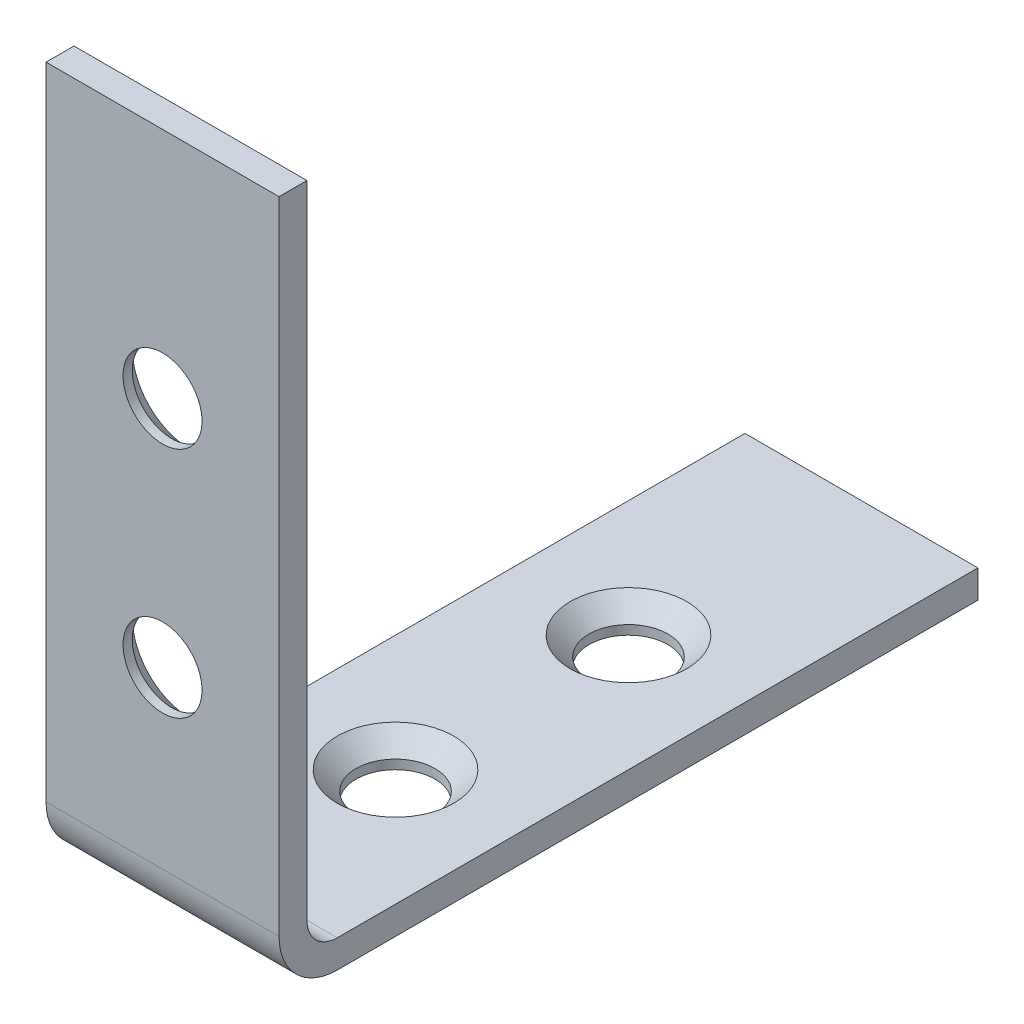
SolidWorks part; units mm, degrees
material "Galvanized Steel"
ref_plane "Front Plane" through (0, 0, 0) normal (0, 0, 1) x (1, 0, 0)
ref_plane "Top Plane" through (0, 0, 0) normal (0, 1, 0) x (1, 0, 0)
ref_plane "Right Plane" through (0, 0, 0) normal (1, 0, 0) x (0, 0, -1)
sketch "Sketch1" plane through (0, 0, 0) normal (1, 0, 0) x (0, 0, -1)
  line L0 (0, 3.175) -> (0, 38.1)
  line L1 (0, 38.1) -> (1.524, 38.1)
  line L2 (1.524, 38.1) -> (1.524, 3.175)
  line L3 (3.175, 1.524) -> (38.1, 1.524)
  line L4 (38.1, 1.524) -> (38.1, 0)
  line L5 (38.1, 0) -> (3.175, 0)
  arc A0 (0, 3.175) -> (3.175, 0) centre (3.175, 3.175) ccw
  arc A1 (1.524, 3.175) -> (3.175, 1.524) centre (3.175, 3.175) ccw
  point P9 (0, 0)
  dimension "D3" = 3.175
  dimension "D1" = 38.1
  dimension "D2" = 1.524
extrude "Boss-Extrude1" add sketch "Sketch1" along normal mid plane 12.7
hole_wizard "#6 Clearance Hole1" positions "Sketch2" profile "Sketch3" hole size "#6" standard "ANSI Inch" end condition through all
sketch "Sketch2" plane through (0, 1.524, 0) normal (0, 1, 0) x (1, 0, 0)
  line L0 (6.35, 38.1) -> (-6.35, 38.1) construction
  line L1 (0, 38.1) -> (0, 25.4) construction
  line L2 (0, 25.4) -> (0, 12.7) construction
  line L3 (0, 12.7) -> (0, 0) construction
  point P0 (0, 25.4)
  point P2 (0, 12.7)
sketch "Sketch3" plane through (0, 1.524, -25.4) normal (1, 0, 0) x (0, 0, 1)
  line L0 (0, 0) -> (0, 1.524)
  line L1 (0, 1.524) -> (2.1526, 1.524)
  line L2 (2.1526, 1.524) -> (2.1526, 1.0223)
  line L3 (2.1526, 1.0223) -> (3.175, 0)
  line L5 (3.175, 0) -> (0, 0)
  line L6 (-2.1526, 1.0223) -> (-3.175, 0) construction
  line L11 (0, -6.35) -> (0, 107.95) construction
  dimension "Thru Hole Dia." = 4.3053
  dimension "Thru Hole Depth" = 1.524
  dimension "Near C'Sink Dia." = 6.35
  dimension "Near C'Sink Angle" = 90
hole_wizard "#6 Clearance Hole2" positions "Sketch5" profile "Sketch6" hole size "#6" standard "ANSI Inch" end condition through all
sketch "Sketch5" plane through (0, 0, -1.524) normal (0, 0, -1) x (-1, 0, 0)
  line L0 (0, 0) -> (0, 12.7) construction
  line L1 (0, 12.7) -> (0, 25.4) construction
  line L2 (0, 25.4) -> (0, 38.1) construction
  line L3 (-6.35, 38.1) -> (6.35, 38.1) construction
  point P0 (0, 12.7)
  point P2 (0, 25.4)
sketch "Sketch6" plane through (0, 12.7, -1.524) normal (1, 0, 0) x (0, 1, 0)
  line L0 (0, 0) -> (0, 1.524)
  line L1 (0, 1.524) -> (2.1526, 1.524)
  line L2 (2.1526, 1.524) -> (2.1526, 1.0223)
  line L3 (2.1526, 1.0223) -> (3.175, 0)
  line L5 (3.175, 0) -> (0, 0)
  line L6 (-2.1526, 1.0223) -> (-3.175, 0) construction
  line L11 (0, -6.35) -> (0, 107.95) construction
  dimension "Thru Hole Dia." = 4.3053
  dimension "Thru Hole Depth" = 1.524
  dimension "Near C'Sink Dia." = 6.35
  dimension "Near C'Sink Angle" = 90
